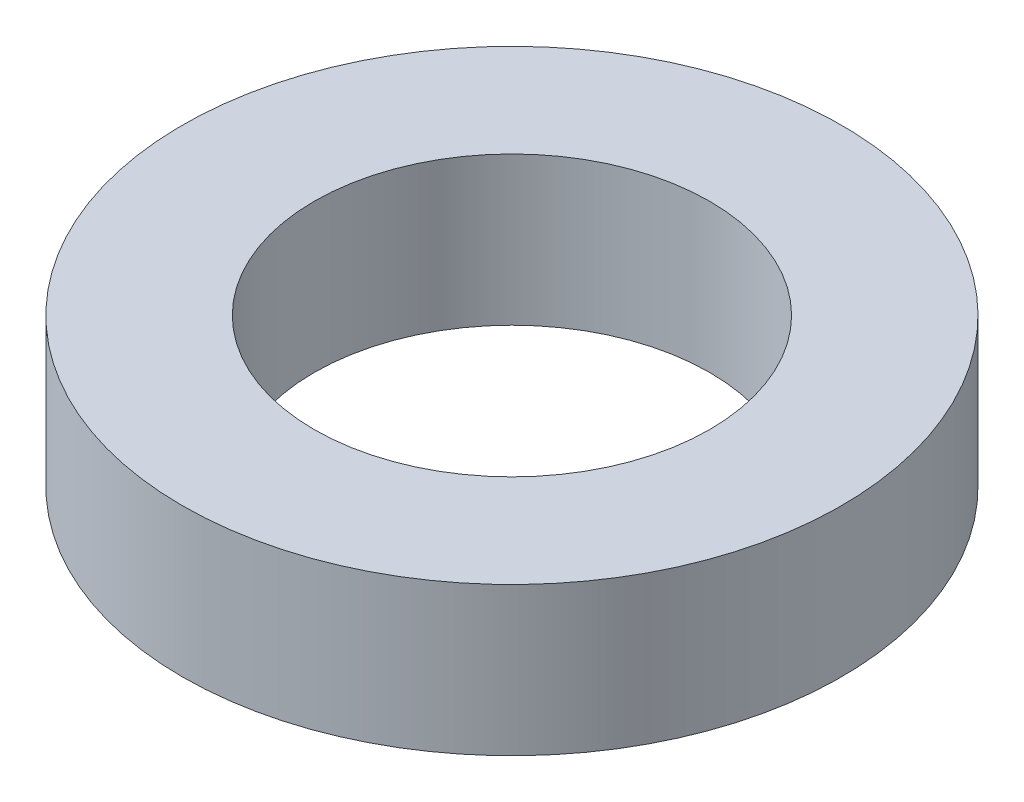
SolidWorks part; units mm, degrees
ref_plane "Front Plane" through (0, 0, 0) normal (0, 0, 1) x (1, 0, 0)
ref_plane "Top Plane" through (0, 0, 0) normal (0, 1, 0) x (1, 0, 0)
ref_plane "Right Plane" through (0, 0, 0) normal (1, 0, 0) x (0, 0, -1)
sketch "Sketch1" plane through (0, 0, 0) normal (0, 1, 0) x (1, 0, 0)
  circle A0 centre (0, 0) radius 6
  circle A1 centre (0, 0) radius 10
  dimension "D1" = 12
  dimension "D2" = 20
extrude "Boss-Extrude1" add sketch "Sketch1" along normal blind 4.5
